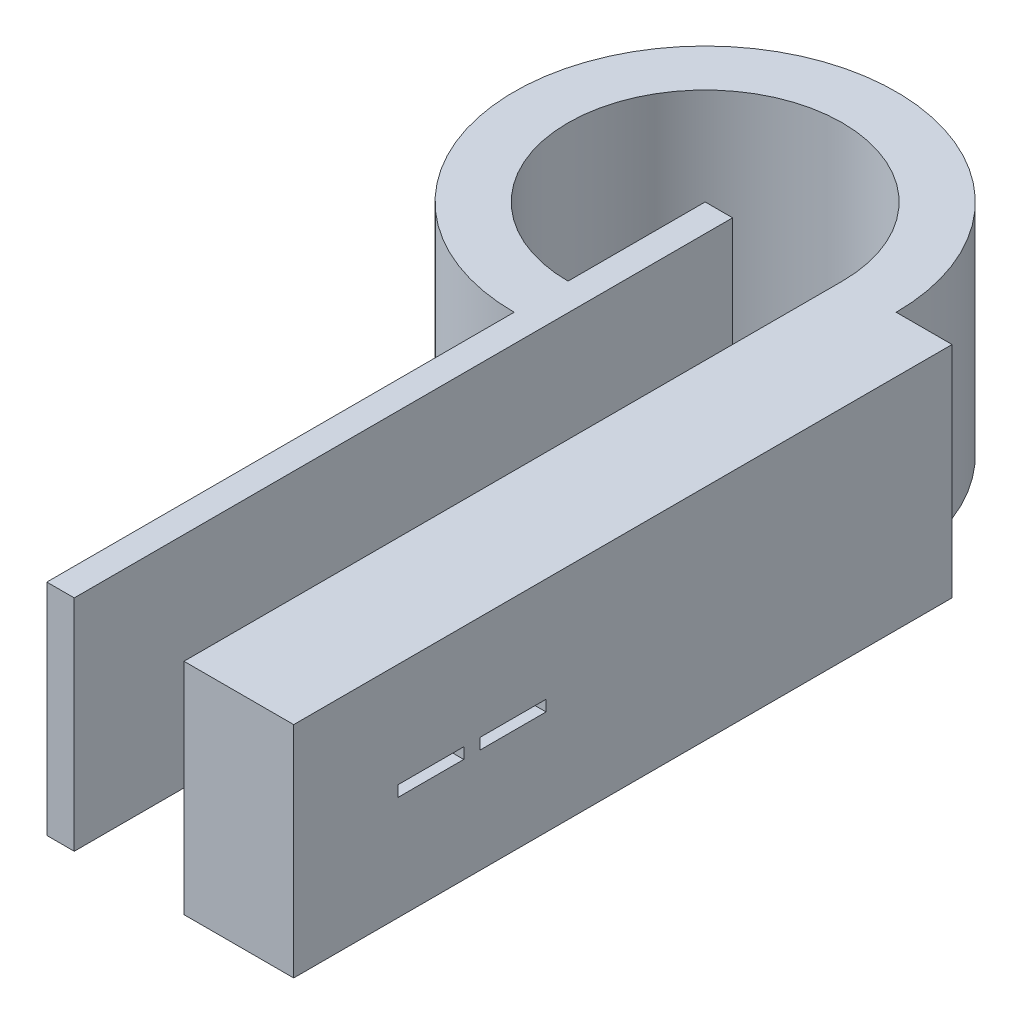
SolidWorks part; units mm, degrees
ref_plane "Front Plane" through (0, 0, 0) normal (0, 0, 1) x (1, 0, 0)
ref_plane "Top Plane" through (0, 0, 0) normal (0, 1, 0) x (1, 0, 0)
ref_plane "Right Plane" through (0, 0, 0) normal (1, 0, 0) x (0, 0, -1)
sketch "Sketch1" plane through (0, 0, 0) normal (0, 1, 0) x (1, 0, 0)
  line L1 (-43.8012, 22.7489) -> (-41.3012, 22.7489)
  line L2 (-43.8012, 22.7489) -> (-43.8012, -37.2511)
  line L3 (-43.8012, -37.2511) -> (-41.3012, -37.2511)
  line L4 (-41.3012, 22.7489) -> (-41.3012, -37.2511)
  line L5 (-31.3012, 22.7489) -> (-21.3012, 22.7489)
  line L6 (-31.3012, 22.7489) -> (-31.3012, -37.2511)
  line L7 (-31.3012, -37.2511) -> (-21.3012, -37.2511)
  line L8 (-21.3012, 22.7489) -> (-21.3012, -37.2511)
  arc A0 (-26.3923, 22.7489) -> (-43.8012, 5.34) centre (-43.8012, 22.7489) ccw
  arc A1 (-31.3012, 22.7489) -> (-43.8012, 10.2489) centre (-43.8012, 22.7489) ccw
  point P8 (-42.5512, -37.2511)
  point P9 (-31.3012, -7.2511)
  dimension "D1" = 60
  dimension "D2" = 60
  dimension "D3" = 10
  dimension "D4" = 10
  dimension "D5" = 2.5
extrude "Boss-Extrude1" add sketch "Sketch1" along normal blind 20
sketch "Sketch2" plane through (-31.3012, 0, 0) normal (-1, 0, 0) x (0, 0, 1)
  line L0 (-5.34, 20) -> (37.2511, 20) construction
  line L5 (37.2511, 20) -> (37.2511, 0) construction
  circle A0 centre (24.7511, 10) radius 2.6
  circle A1 centre (17.2511, 10) radius 4
  dimension "D5" = 10
  dimension "D7" = 7.5
  dimension "D6" = 10
  dimension "D8" = 12.5
extrude "Cut-Extrude2" cut sketch "Sketch2" against normal blind 8 contours A1
sketch "Sketch3" plane through (-21.3012, 0, 0) normal (1, 0, 0) x (0, 0, -1)
  line L0 (-27.7511, 10.5) -> (-21.7511, 9.5)
  line L1 (-27.7511, 9.5) -> (-21.7511, 10.5)
  line L2 (-20.2511, 10.5) -> (-14.2511, 9.5)
  line L3 (-14.2511, 10.5) -> (-20.2511, 10.5)
  line L4 (-14.2511, 10.5) -> (-14.2511, 9.5)
  line L5 (-14.2511, 9.5) -> (-20.2511, 9.5)
  line L6 (-20.2511, 10.5) -> (-20.2511, 9.5)
  line L7 (-21.7511, 10.5) -> (-27.7511, 10.5)
  line L8 (-21.7511, 10.5) -> (-21.7511, 9.5)
  line L9 (-21.7511, 9.5) -> (-27.7511, 9.5)
  line L10 (-27.7511, 10.5) -> (-27.7511, 9.5)
  line L11 (-20.2511, 9.5) -> (-14.2511, 10.5)
  line L12 (-37.2511, 20) -> (-37.2511, 0) construction
  line L13 (22.7489, 20) -> (-37.2511, 20) construction
  point P2 (-24.7511, 10)
  point P3 (-17.2511, 10)
  point P7 (-34.8606, 19.8466)
  dimension "D1" = 6
  dimension "D2" = 6
  dimension "D3" = 12.5
  dimension "D4" = 7.5
  dimension "D5" = 10
  dimension "D6" = 10
  dimension "D7" = 1
extrude "Cut-Extrude4" cut sketch "Sketch3" against normal blind 10 contours L0 L10 L1 | L1 L7 L0 | L8 L1 L0 | L9 L0 L1 | L6 L11 L2 | L11 L2 L4 | L2 L11 L3 | L11 L5 L2
sketch "Sketch4" plane through (-31.3012, 0, 0) normal (-1, 0, 0) x (0, 0, 1)
  line L0 (37.2511, 20) -> (37.2511, 0) construction
  line L1 (-5.34, 20) -> (37.2511, 20) construction
  circle A0 centre (24.7511, 10) radius 2.6
  dimension "D1" = 12.5
  dimension "D2" = 10
extrude "Cut-Extrude5" cut sketch "Sketch4" against normal blind 1.5
